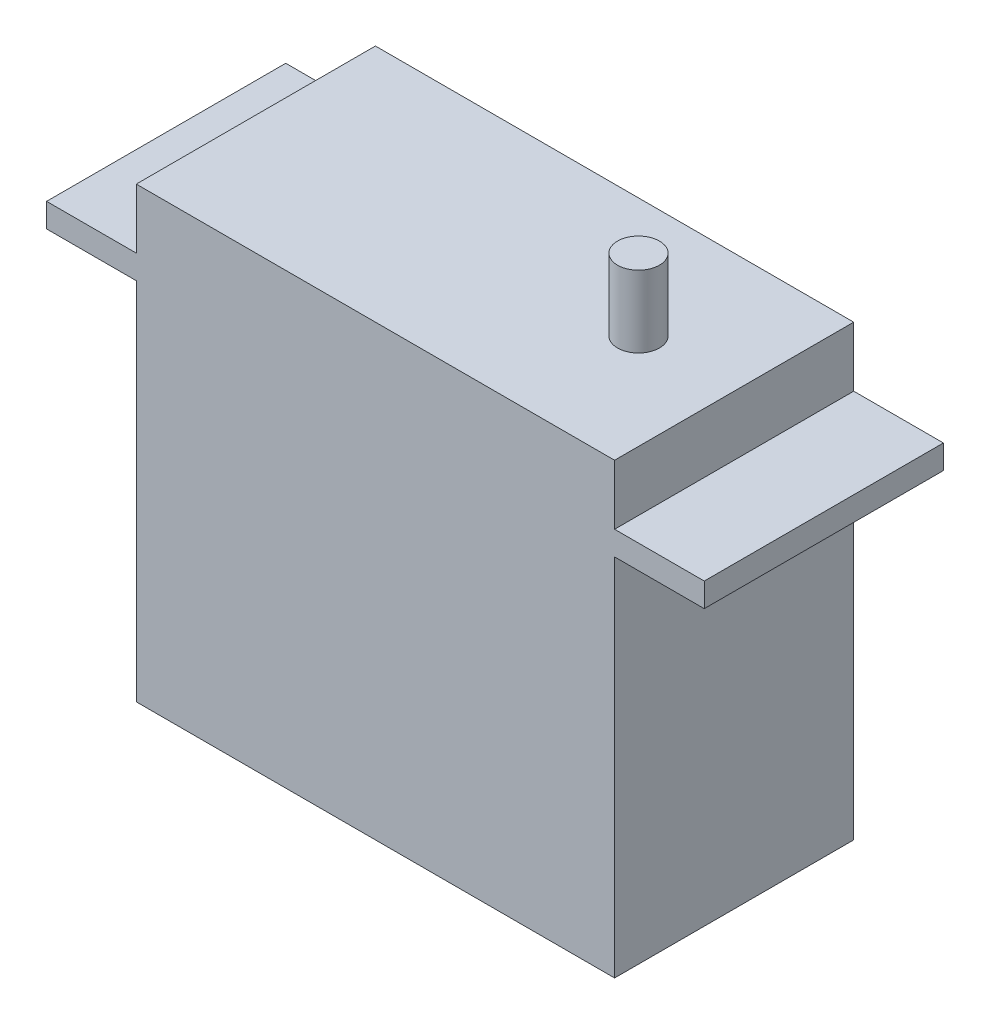
SolidWorks part; units mm, degrees
ref_plane "Front" through (0, 0, 0) normal (0, 0, 1) x (1, 0, 0)
ref_plane "Top" through (0, 0, 0) normal (0, 1, 0) x (1, 0, 0)
ref_plane "Right" through (0, 0, 0) normal (1, 0, 0) x (0, 0, -1)
sketch "Sketch1" plane through (0, 0, 0) normal (0, 1, 0) x (1, 0, 0)
  line L1 (0, 0) -> (40, 0)
  line L2 (0, 0) -> (0, -20)
  line L3 (0, -20) -> (40, -20)
  line L4 (40, 0) -> (40, -20)
  dimension "D1" = 40
  dimension "D2" = 20
extrude "Boss-Extrude1" add sketch "Sketch1" along normal blind 37.5
sketch "Sketch2" plane through (40, 0, 0) normal (1, 0, 0) x (0, 0, -1)
  line L0 (-20, 37.5) -> (-20, 0) construction
  line L1 (-20, 32.5) -> (0, 32.5)
  line L2 (-20, 32.5) -> (-20, 30.5)
  line L3 (-20, 30.5) -> (0, 30.5)
  line L4 (0, 32.5) -> (0, 30.5)
  line L5 (0, 37.5) -> (0, 0) construction
  line L6 (-20, 37.5) -> (0, 37.5) construction
  dimension "D1" = 2
  dimension "D2" = 5
extrude "Boss-Extrude2" add sketch "Sketch2" along normal blind 7.5
sketch "Sketch3" plane through (0, 0, 0) normal (-1, 0, 0) x (0, 0, 1)
  line L0 (0, 37.5) -> (0, 0) construction
  line L1 (0, 32.5) -> (20, 32.5)
  line L2 (0, 32.5) -> (0, 30.5)
  line L3 (0, 30.5) -> (20, 30.5)
  line L4 (20, 32.5) -> (20, 30.5)
  line L5 (20, 37.5) -> (20, 0) construction
  line L6 (0, 37.5) -> (20, 37.5) construction
  dimension "D1" = 2
  dimension "D2" = 5
extrude "Boss-Extrude3" add sketch "Sketch3" along normal blind 7.5
sketch "Sketch4" plane through (0, 37.5, 0) normal (0, 1, 0) x (1, 0, 0)
  line L0 (40, 0) -> (0, 0) construction
  line L1 (40, -20) -> (40, 0) construction
  circle A0 centre (32, -10) radius 1.75
  dimension "D1" = 3.5
  dimension "D2" = 10
  dimension "D3" = 8
extrude "Boss-Extrude4" add sketch "Sketch4" along normal blind 6
